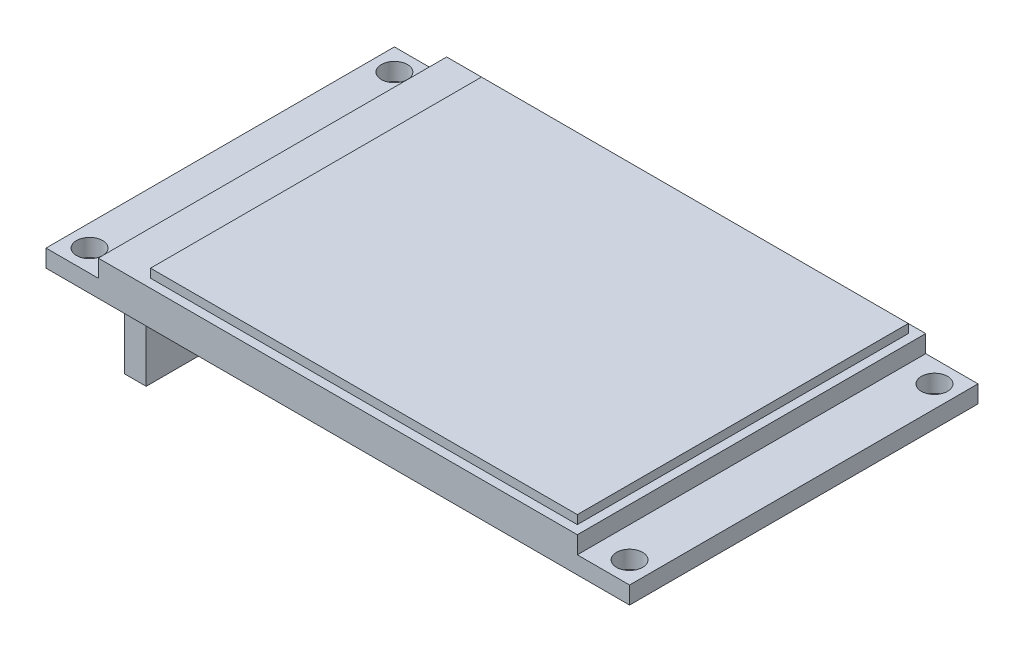
SolidWorks part; units mm, degrees
ref_plane "Front Plane" through (0, 0, 0) normal (0, 0, 1) x (1, 0, 0)
ref_plane "Top Plane" through (0, 0, 0) normal (0, 1, 0) x (1, 0, 0)
ref_plane "Right Plane" through (0, 0, 0) normal (1, 0, 0) x (0, 0, -1)
sketch "Sketch1" plane through (0, 0, 0) normal (0, 1, 0) x (1, 0, 0)
  line L1 (0, 0) -> (67, 0)
  line L2 (0, 0) -> (0, 40)
  line L3 (0, 40) -> (67, 40)
  line L4 (67, 0) -> (67, 40)
  dimension "D1" = 67
  dimension "D2" = 40
extrude "Boss-Extrude1" add sketch "Sketch1" along normal blind 2
sketch "Sketch2" plane through (0, 2, 0) normal (0, 1, 0) x (1, 0, 0)
  line L0 (0, 40) -> (0, 0) construction
  line L1 (6, 40) -> (61, 40)
  line L2 (6, 40) -> (6, 0)
  line L3 (6, 0) -> (61, 0)
  line L4 (61, 40) -> (61, 0)
  line L6 (67, 40) -> (0, 40) construction
  dimension "D1" = 55
  dimension "D2" = 40
  dimension "D3" = 6
  dimension "D4" = 0
extrude "Boss-Extrude2" add sketch "Sketch2" along normal blind 2 contours L2 L1 L4 L3
sketch "Sketch3" plane through (0, 4, 0) normal (0, 1, 0) x (1, 0, 0)
  line L0 (6, 40) -> (6, 0) construction
  line L1 (60, 1) -> (11, 1)
  line L2 (60, 1) -> (60, 39)
  line L3 (60, 39) -> (11, 39)
  line L4 (11, 1) -> (11, 39)
  line L5 (6, 40) -> (61, 40) construction
  line L6 (61, 40) -> (61, 0) construction
  line L7 (6, 0) -> (61, 0) construction
  dimension "D1" = 5
  dimension "D2" = 1
  dimension "D3" = 1
  dimension "D4" = 1
extrude "Boss-Extrude4" add sketch "Sketch3" along normal blind 1
sketch "Sketch4" plane through (0, 2, 0) normal (0, 1, 0) x (1, 0, 0)
  line L1 (0, 40) -> (0, 0) construction
  line L2 (6, 40) -> (0, 40) construction
  circle A0 centre (2.5, 37.5) radius 1.5
  dimension "D1" = 3
  dimension "D2" = 2.5
  dimension "D3" = 2.5
extrude "Cut-Extrude1" cut sketch "Sketch4" against normal up to next contours A0
sketch "Sketch5" plane through (0, 2, 0) normal (0, 1, 0) x (1, 0, 0)
  line L0 (0, 40) -> (0, 0) construction
  line L1 (0, 0) -> (6, 0) construction
  circle A0 centre (2.5, 2.5) radius 1.5
  point P6 (3.3187, 5.0339)
  dimension "D1" = 3
  dimension "D2" = 2.5
  dimension "D3" = 2.5
extrude "Cut-Extrude2" cut sketch "Sketch5" against normal up to next
sketch "Sketch6" plane through (0, 2, 0) normal (0, 1, 0) x (1, 0, 0)
  line L0 (67, 40) -> (61, 40) construction
  line L1 (67, 0) -> (67, 40) construction
  circle A0 centre (64.5, 37.5) radius 1.5
  dimension "D1" = 3
  dimension "D2" = 2.5
  dimension "D3" = 2.5
extrude "Cut-Extrude3" cut sketch "Sketch6" against normal up to next
sketch "Sketch7" plane through (0, 2, 0) normal (0, 1, 0) x (1, 0, 0)
  line L0 (61, 0) -> (67, 0) construction
  line L1 (67, 0) -> (67, 40) construction
  circle A0 centre (64.5, 2.5) radius 1.5
  dimension "D1" = 3
  dimension "D2" = 2.5
  dimension "D3" = 2.5
extrude "Cut-Extrude4" cut sketch "Sketch7" against normal up to next
sketch "Sketch9" plane through (0, 0, 0) normal (0, -1, 0) x (-1, 0, 0)
  line L0 (0, 40) -> (0, 0) construction
  line L1 (0, 9) -> (-2.5, 9)
  line L2 (0, 9) -> (0, 34)
  line L3 (0, 34) -> (-2.5, 34)
  line L4 (-2.5, 9) -> (-2.5, 34)
  line L5 (0, 0) -> (-67, 0) construction
  dimension "D1" = 25
  dimension "D2" = 9
  dimension "D3" = 2.5
extrude "Boss-Extrude7" add sketch "Sketch9" along normal blind 15
